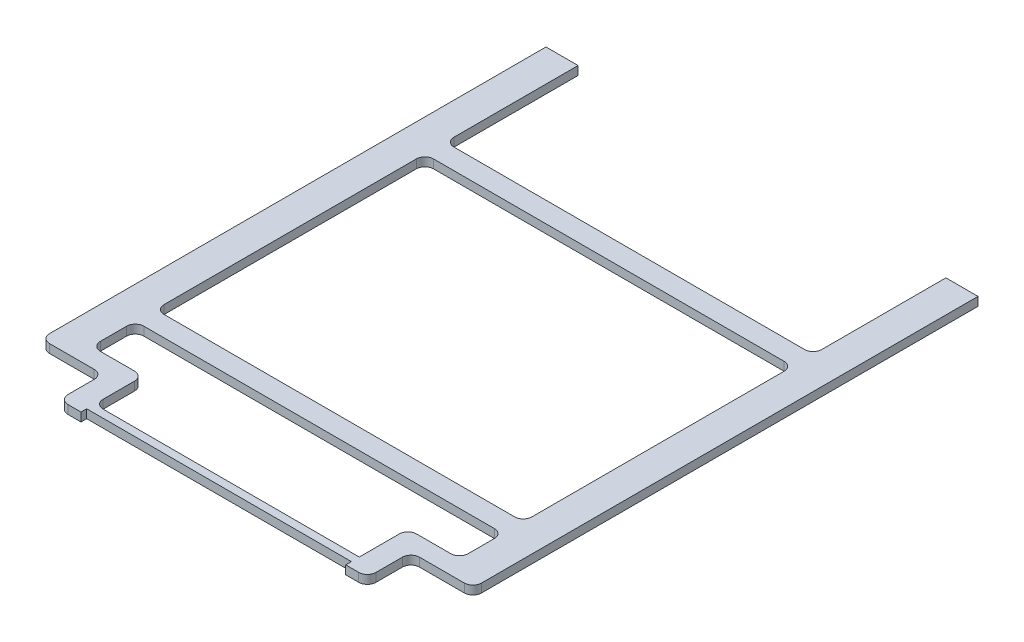
SolidWorks part; units mm, degrees
ref_plane "前视基准面" through (0, 0, 0) normal (0, 0, 1) x (1, 0, 0)
ref_plane "上视基准面" through (0, 0, 0) normal (0, 1, 0) x (1, 0, 0)
ref_plane "右视基准面" through (0, 0, 0) normal (1, 0, 0) x (0, 0, -1)
sketch "草图1" plane through (0, 0, 0) normal (0, 1, 0) x (1, 0, 0)
  line L0 (-50.2436, -63.5) -> (49.7564, -63.5)
  line L1 (49.7564, -63.5) -> (49.7564, 63.5)
  line L2 (49.7564, 63.5) -> (-50.2436, 63.5)
  line L3 (-50.2436, 63.5) -> (-50.2436, -63.5)
  line L4 (35.0018, 52.6252) -> (35.0018, 53.3252)
  line L5 (34.5018, 53.3252) -> (34.5018, 52.6252)
  line L6 (37.0018, 55.6252) -> (37.0018, 56.3252)
  line L7 (36.5018, 56.3252) -> (36.5018, 55.6252)
  line L8 (32.8018, 60.8252) -> (33.5018, 60.8252)
  line L9 (33.5018, 61.3252) -> (32.8018, 61.3252)
  line L10 (31.8018, 52.6252) -> (31.8018, 53.3252)
  line L11 (31.3018, 53.3252) -> (31.3018, 52.6252)
  line L12 (17.9132, 52.6252) -> (17.9132, 53.3252)
  line L13 (17.4132, 53.3252) -> (17.4132, 52.6252)
  line L14 (28.9018, 52.6252) -> (28.9018, 53.3252)
  line L15 (28.4018, 53.3252) -> (28.4018, 52.6252)
  line L16 (21.1132, 52.6252) -> (21.1132, 53.3252)
  line L17 (20.6132, 53.3252) -> (20.6132, 52.6252)
  line L18 (16.3132, 54.6252) -> (16.3132, 55.3252)
  line L19 (15.8132, 55.3252) -> (15.8132, 54.6252)
  line L20 (15.0132, 52.6252) -> (15.0132, 53.3252)
  line L21 (14.5132, 53.3252) -> (14.5132, 52.6252)
  line L22 (30.2018, 54.6252) -> (30.2018, 55.3252)
  line L23 (29.7018, 55.3252) -> (29.7018, 54.6252)
  line L24 (23.1132, 55.6252) -> (23.1132, 56.3252)
  line L25 (22.6132, 56.3252) -> (22.6132, 55.6252)
  line L26 (18.9132, 60.8252) -> (19.6132, 60.8252)
  line L27 (19.6132, 61.3252) -> (18.9132, 61.3252)
  line L28 (-25.4838, 56.3252) -> (-25.4838, 54.6252)
  line L29 (-24.6838, 54.6252) -> (-24.6838, 56.3252)
  line L30 (-28.6838, 53.1752) -> (-30.8838, 53.1752)
  line L31 (-30.8838, 52.3752) -> (-28.6838, 52.3752)
  line L32 (-28.6838, 59.3752) -> (-30.8838, 59.3752)
  line L33 (-30.8838, 58.5752) -> (-28.6838, 58.5752)
  line L34 (-0.2436, 12.4244) -> (-0.2436, 7.9949) construction
  line L35 (-50.2436, 63.5) -> (-42.8098, 63.5)
  line L36 (-50.2436, 63.5) -> (-50.2436, -53.4162)
  line L37 (-50.2436, -53.4162) -> (-42.8098, -53.4162)
  line L38 (-42.8098, 63.5) -> (-42.8098, -53.4162)
  line L39 (49.7564, -53.4162) -> (42.3226, -53.4162)
  line L40 (42.3226, 28.0427) -> (-42.8098, 28.0427)
  line L41 (-0.2436, 28.0427) -> (-0.2436, 32.7788)
  line L42 (42.3226, 32.7788) -> (-42.8098, 32.7788)
  line L43 (-42.8098, 28.0427) -> (-42.8098, 32.7788)
  line L44 (-42.8098, -53.4162) -> (-35.899, -53.4162)
  line L45 (-42.8098, -53.4162) -> (-42.8098, -49.0976)
  line L46 (-42.8098, -49.0976) -> (-35.899, -49.0976)
  line L47 (-35.899, -53.4162) -> (-35.899, -49.0976)
  line L48 (-35.899, -53.4162) -> (-30.8838, -53.4162)
  line L49 (-35.899, -53.4162) -> (-35.899, -63.5)
  line L50 (-35.899, -63.5) -> (-30.8838, -63.5)
  line L51 (-30.8838, -53.4162) -> (-30.8838, -63.5)
  line L52 (-35.899, -49.0976) -> (-30.8838, -49.0976)
  line L53 (-35.899, -49.0976) -> (-35.899, -53.4162)
  line L54 (-35.899, -53.4162) -> (-30.8838, -53.4162)
  line L55 (-30.8838, -49.0976) -> (-30.8838, -53.4162)
  line L56 (42.3226, -39.0173) -> (-42.8098, -39.0173)
  line L57 (-0.2436, -39.0173) -> (-0.2436, -34.3293)
  line L58 (42.3226, -34.3293) -> (-42.8098, -34.3293)
  line L59 (-42.8098, -39.0173) -> (-42.8098, -34.3293)
  line L60 (35.4118, -53.4162) -> (35.4118, -63.5)
  line L61 (35.4118, -53.4162) -> (30.3966, -53.4162)
  line L62 (35.4118, -49.0976) -> (30.3966, -49.0976)
  line L63 (35.4118, -53.4162) -> (30.3966, -53.4162)
  line L64 (30.3966, -53.4162) -> (30.3966, -63.5)
  line L65 (30.3966, -49.0976) -> (30.3966, -53.4162)
  line L66 (35.4118, -49.0976) -> (35.4118, -53.4162)
  line L67 (35.4118, -53.4162) -> (35.4118, -49.0976)
  line L68 (42.3226, -53.4162) -> (42.3226, -49.0976)
  line L69 (42.3226, -49.0976) -> (35.4118, -49.0976)
  line L70 (42.3226, -53.4162) -> (35.4118, -53.4162)
  line L71 (42.3226, 63.5) -> (42.3226, -53.4162)
  line L72 (42.3226, 28.0427) -> (42.3226, 32.7788)
  line L74 (-30.8838, -60.3622) -> (30.3966, -60.3622)
  line L75 (-30.8838, -60.3622) -> (-30.8838, -62.1901)
  line L76 (-30.8838, -62.1901) -> (30.3966, -62.1901)
  line L77 (30.3966, -60.3622) -> (30.3966, -62.1901)
  circle A0 centre (44.7564, -58.5) radius 1.5875
  circle A1 centre (33.4384, -32.5) radius 0.6
  circle A2 centre (33.4384, -41) radius 0.6
  circle A3 centre (22.6164, -23.8745) radius 0.55
  circle A4 centre (22.6164, -10.2855) radius 0.55
  circle A5 centre (22.6164, -18.8745) radius 0.55
  circle A6 centre (34.9862, 35.1428) radius 0.4
  circle A7 centre (28.8902, 40.1428) radius 0.4
  circle A8 centre (28.8902, 35.1428) radius 0.4
  circle A9 centre (22.6164, -5.2855) radius 0.55
  circle A10 centre (22.9034, 40.1428) radius 0.4
  circle A11 centre (22.9034, 35.1428) radius 0.4
  circle A12 centre (15.5298, -57.9882) radius 0.75
  circle A13 centre (20.9384, -32.5) radius 0.6
  circle A14 centre (20.9384, -41) radius 0.6
  circle A15 centre (15.5298, -52.9082) radius 0.75
  circle A16 centre (15.1504, -32.5) radius 0.6
  circle A17 centre (15.1504, -41) radius 0.6
  circle A18 centre (22.6164, 3.3035) radius 0.55
  circle A19 centre (22.6164, 8.3035) radius 0.55
  circle A20 centre (19.3906, 24.464) radius 0.45
  circle A21 centre (16.8506, 24.464) radius 0.45
  circle A22 centre (16.8158, 35.1428) radius 0.4
  circle A23 centre (14.3106, 24.464) radius 0.45
  circle A24 centre (34.9862, 40.1428) radius 0.4
  circle A25 centre (34.6306, 47.2948) radius 0.45
  circle A26 centre (34.6306, 44.7548) radius 0.45
  circle A27 centre (31.7096, 44.7548) radius 0.45
  circle A28 centre (34.6306, 49.8348) radius 0.45
  circle A29 centre (31.7096, 47.2948) radius 0.45
  arc A30 (35.0018, 53.3252) -> (34.5018, 53.3252) centre (34.7518, 53.3252) ccw
  arc A31 (34.5018, 52.6252) -> (35.0018, 52.6252) centre (34.7518, 52.6252) ccw
  arc A32 (37.0018, 56.3252) -> (36.5018, 56.3252) centre (36.7518, 56.3252) ccw
  arc A33 (36.5018, 55.6252) -> (37.0018, 55.6252) centre (36.7518, 55.6252) ccw
  circle A34 centre (36.1518, 59.9752) radius 0.6
  circle A35 centre (31.7096, 49.8348) radius 0.45
  arc A36 (33.5018, 60.8252) -> (33.5018, 61.3252) centre (33.5018, 61.0752) ccw
  arc A37 (32.8018, 61.3252) -> (32.8018, 60.8252) centre (32.8018, 61.0752) ccw
  arc A38 (31.8018, 53.3252) -> (31.3018, 53.3252) centre (31.5518, 53.3252) ccw
  arc A39 (31.3018, 52.6252) -> (31.8018, 52.6252) centre (31.5518, 52.6252) ccw
  arc A40 (17.9132, 53.3252) -> (17.4132, 53.3252) centre (17.6632, 53.3252) ccw
  arc A41 (17.4132, 52.6252) -> (17.9132, 52.6252) centre (17.6632, 52.6252) ccw
  arc A42 (28.9018, 53.3252) -> (28.4018, 53.3252) centre (28.6518, 53.3252) ccw
  arc A43 (28.4018, 52.6252) -> (28.9018, 52.6252) centre (28.6518, 52.6252) ccw
  arc A44 (21.1132, 53.3252) -> (20.6132, 53.3252) centre (20.8632, 53.3252) ccw
  arc A45 (20.6132, 52.6252) -> (21.1132, 52.6252) centre (20.8632, 52.6252) ccw
  circle A46 centre (16.8158, 40.1428) radius 0.4
  arc A47 (16.3132, 55.3252) -> (15.8132, 55.3252) centre (16.0632, 55.3252) ccw
  arc A48 (15.8132, 54.6252) -> (16.3132, 54.6252) centre (16.0632, 54.6252) ccw
  arc A49 (15.0132, 53.3252) -> (14.5132, 53.3252) centre (14.7632, 53.3252) ccw
  arc A50 (14.5132, 52.6252) -> (15.0132, 52.6252) centre (14.7632, 52.6252) ccw
  arc A51 (30.2018, 55.3252) -> (29.7018, 55.3252) centre (29.9518, 55.3252) ccw
  arc A52 (29.7018, 54.6252) -> (30.2018, 54.6252) centre (29.9518, 54.6252) ccw
  circle A53 centre (29.6518, 59.9752) radius 0.6
  arc A54 (23.1132, 56.3252) -> (22.6132, 56.3252) centre (22.8632, 56.3252) ccw
  arc A55 (22.6132, 55.6252) -> (23.1132, 55.6252) centre (22.8632, 55.6252) ccw
  circle A56 centre (22.2632, 59.9752) radius 0.6
  arc A57 (19.6132, 60.8252) -> (19.6132, 61.3252) centre (19.6132, 61.0752) ccw
  arc A58 (18.9132, 61.3252) -> (18.9132, 60.8252) centre (18.9132, 61.0752) ccw
  circle A59 centre (15.7632, 59.9752) radius 0.6
  circle A60 centre (6.4274, -59.0362) radius 0.4
  circle A61 centre (6.4274, -55.1319) radius 0.4
  circle A62 centre (1.4274, -59.0362) radius 0.4
  circle A63 centre (-1.8346, -59.0362) radius 0.4
  circle A64 centre (1.4274, -55.1319) radius 0.4
  circle A65 centre (-1.8346, -55.1319) radius 0.4
  circle A66 centre (6.4274, -50.332) radius 0.4
  circle A67 centre (2.6504, -32.5) radius 0.6
  circle A68 centre (2.6504, -41) radius 0.6
  circle A69 centre (1.4274, -50.332) radius 0.4
  circle A70 centre (-1.8346, -50.332) radius 0.4
  circle A71 centre (-3.1376, -32.5) radius 0.6
  circle A72 centre (-6.8346, -59.0362) radius 0.4
  circle A73 centre (-6.8346, -50.332) radius 0.4
  circle A74 centre (-6.8346, -55.1319) radius 0.4
  circle A75 centre (-45.2436, -58.5) radius 1.5875
  circle A76 centre (-15.8138, -53.4162) radius 0.75
  circle A77 centre (-15.8138, -58.4962) radius 0.75
  circle A78 centre (-21.4256, -41) radius 0.6
  circle A79 centre (-3.1376, -41) radius 0.6
  circle A80 centre (-15.6376, -41) radius 0.6
  circle A81 centre (-33.9256, -41) radius 0.6
  circle A82 centre (-21.4256, -32.5) radius 0.6
  circle A83 centre (-33.9256, -32.5) radius 0.6
  circle A84 centre (2.2964, 12.4244) radius 0.45
  circle A85 centre (11.6436, 53.1114) radius 0.45
  circle A86 centre (7.478, 24.5148) radius 0.5
  circle A87 centre (-2.7836, 12.4244) radius 0.45
  circle A88 centre (-0.2436, 12.4244) radius 0.45
  circle A89 centre (-0.2436, 46.5) radius 1.5875
  circle A90 centre (7.946, 55.2596) radius 0.75
  circle A91 centre (11.6436, 55.6514) radius 0.45
  circle A92 centre (7.946, 60.2596) radius 0.75
  circle A93 centre (2.946, 55.2596) radius 0.75
  circle A94 centre (5.446, 57.7596) radius 0.75
  circle A95 centre (2.946, 60.2596) radius 0.75
  circle A96 centre (-15.6376, -32.5) radius 0.6
  circle A97 centre (-23.1036, -18.8745) radius 0.55
  circle A98 centre (-23.1036, -23.8745) radius 0.55
  circle A99 centre (-23.1036, -10.2855) radius 0.55
  circle A100 centre (-23.1036, 3.3035) radius 0.55
  circle A101 centre (-23.1036, -5.2855) radius 0.55
  circle A102 centre (-23.1036, 8.3035) radius 0.55
  circle A103 centre (-7.762, 24.5148) radius 0.5
  arc A104 (-25.4838, 54.6252) -> (-24.6838, 54.6252) centre (-25.0838, 54.6252) ccw
  arc A105 (-24.6838, 56.3252) -> (-25.4838, 56.3252) centre (-25.0838, 56.3252) ccw
  arc A106 (-30.8838, 53.1752) -> (-30.8838, 52.3752) centre (-30.8838, 52.7752) ccw
  arc A107 (-28.6838, 52.3752) -> (-28.6838, 53.1752) centre (-28.6838, 52.7752) ccw
  circle A108 centre (-39.893, 54.9656) radius 0.75
  arc A109 (-30.8838, 59.3752) -> (-30.8838, 58.5752) centre (-30.8838, 58.9752) ccw
  arc A110 (-28.6838, 58.5752) -> (-28.6838, 59.3752) centre (-28.6838, 58.9752) ccw
  circle A111 centre (-39.893, 60.0456) radius 0.75
  dimension "D1" = 100
  dimension "D2" = 127
extrude "凸台-拉伸1" add sketch "草图1" along normal blind 2 contours L38 L2 L3 L37 | L57 L58 L38 L56 | L44 L47 L46 L38 | L55 L52 L47 L48 | L51 L48 L49 L0 | L71 L58 L57 L56 | L61 L64 L0 L60 | L70 L68 L69 L66 | L66 L62 L65 L61 | L2 L71 L68 L39 L1 | L71 L42 L41 L40 | L41 L42 L38 L40 | L74 L34 L76 L64 | L34 L74 L51 L76
fillet "圆角1" radius 2 14 edges at (42.3226, 1, -28.0427) (-42.8098, 1, -28.0427) (-42.8098, 1, 34.3293) (42.3226, 1, 34.3293) (-42.8098, 1, 39.0173) (-42.8098, 1, 49.0976) (-30.8838, 1, 49.0976) (-30.8838, 1, 60.3622) (30.3966, 1, 49.0976) (42.3226, 1, 49.0976) (42.3226, 1, 39.0173) (-42.8098, 1, -32.7788) (42.3226, 1, -32.7788) (35.4118, 1, 53.4162)
fillet "圆角2" radius 2 5 edges at (-35.899, 1, 63.5) (-35.899, 1, 53.4162) (35.4118, 1, 63.5) (49.7564, 1, 53.4162) (-50.2436, 1, 53.4162)
